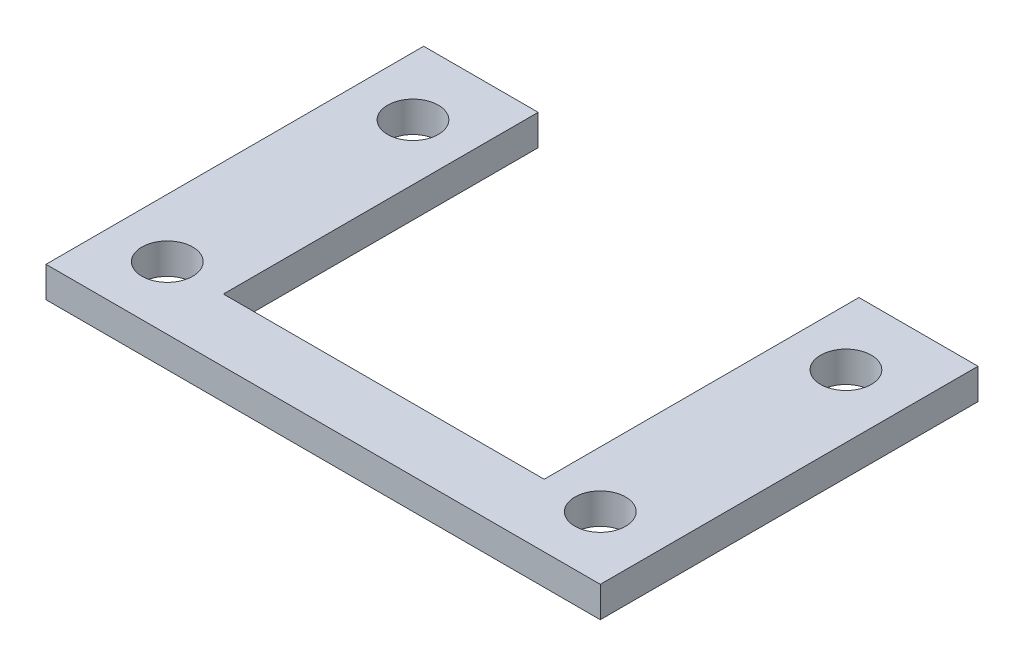
SolidWorks part; units mm, degrees
material "Custom Plastic"
ref_plane "X-Y Datum" through (0, 0, 0) normal (0, 0, 1) x (1, 0, 0)
ref_plane "X-Z Datum" through (0, 0, 0) normal (0, 1, 0) x (1, 0, 0)
ref_plane "Y-Z Datum" through (0, 0, 0) normal (1, 0, 0) x (0, 0, -1)
sketch "Sketch1" plane through (0, 0, 0) normal (0, 1, 0) x (1, 0, 0)
  line L0 (15.5691, 29.1106) -> (25.0351, 29.1106)
  line L1 (15.5691, 29.1106) -> (15.5691, -2.1314)
  line L2 (15.5691, -2.1314) -> (61.4161, -2.1314)
  line L3 (61.4161, 29.1106) -> (61.4161, -2.1314)
  line L4 (22.4951, 23.3956) -> (25.0351, 23.3956) construction
  line L5 (22.4951, 3.0756) -> (25.0351, 3.0756) construction
  line L6 (54.1091, 3.0756) -> (51.5691, 3.0756) construction
  line L7 (54.1091, 23.3956) -> (51.5691, 23.3956) construction
  line L8 (25.0351, 29.1106) -> (25.0351, 3.0756)
  line L9 (25.0351, 3.0756) -> (51.5691, 3.0756)
  line L10 (51.5691, 29.1106) -> (51.5691, 3.0756)
  line L11 (51.5691, 29.1106) -> (61.4161, 29.1106)
  circle A0 centre (20.3951, 23.3956) radius 2.1
  circle A1 centre (20.3951, 3.0756) radius 2.1
  circle A2 centre (56.2091, 23.3956) radius 2.1
  circle A3 centre (56.2091, 3.0756) radius 2.1
extrude "Boss-Extrude1" add sketch "Sketch1" along normal blind 2.54
